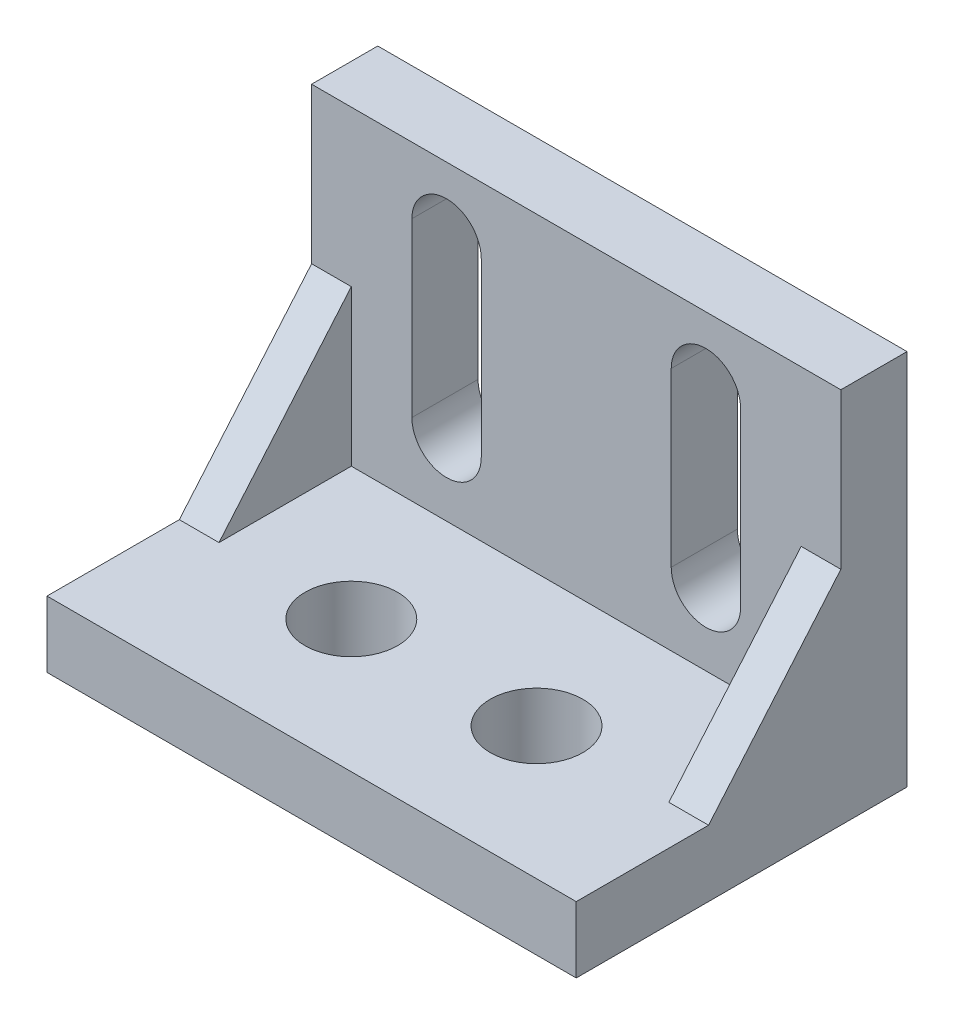
SolidWorks part; units mm, degrees
ref_plane "Front Plane" through (0, 0, 0) normal (0, 0, 1) x (1, 0, 0)
ref_plane "Top Plane" through (0, 0, 0) normal (0, 1, 0) x (1, 0, 0)
ref_plane "Right Plane" through (0, 0, 0) normal (1, 0, 0) x (0, 0, -1)
sketch "Sketch1" plane through (0, 0, 0) normal (0, 0, 1) x (1, 0, 0)
  line L0 (3.25, -4.85) -> (-3.25, -4.85) construction
  line L1 (-10, -10.9397) -> (10, -10.9397)
  line L2 (-10, -10.9397) -> (-10, 3.3116)
  line L3 (-10, 3.3116) -> (10, 3.3116)
  line L4 (10, -10.9397) -> (10, 3.3116)
  line L5 (0, -4.85) -> (0, -10.9397) construction
  line L6 (-4.9, -5.7035) -> (-4.9, 0.8035) construction
  line L7 (-62.56, -10.9397) -> (-56.86, -10.9397) construction
  line L8 (-6.2107, -5.7035) -> (-6.2107, 0.8035)
  line L9 (-3.5893, -5.7035) -> (-3.5893, 0.8035)
  line L10 (4.9, -5.7035) -> (4.9, 0.8035) construction
  line L11 (3.5893, -5.7035) -> (3.5893, 0.8035)
  line L12 (6.2107, -5.7035) -> (6.2107, 0.8035)
  arc A0 (-6.2107, -5.7035) -> (-3.5893, -5.7035) centre (-4.9, -5.7035) ccw
  arc A1 (-3.5893, 0.8035) -> (-6.2107, 0.8035) centre (-4.9, 0.8035) ccw
  arc A3 (3.5893, -5.7035) -> (6.2107, -5.7035) centre (4.9, -5.7035) ccw
  arc A4 (6.2107, 0.8035) -> (3.5893, 0.8035) centre (4.9, 0.8035) ccw
  point P0 (0, -4.85)
  point P14 (-4.9, -2.45)
  point P21 (4.9, -2.45)
  dimension "D1" = 20
extrude "Boss-Extrude1" add sketch "Sketch1" along normal blind 2.5 contours L1 L4 L3 L2
sketch "Sketch2" plane through (0, 0, 2.5) normal (0, 0, 1) x (1, 0, 0)
  line L0 (10, -10.9397) -> (10, 3.3116) construction
  line L1 (-10, -10.9397) -> (10, -10.9397)
  line L2 (-10, -10.9397) -> (-10, -8.4397)
  line L3 (-10, -8.4397) -> (10, -8.4397)
  line L4 (10, -10.9397) -> (10, -8.4397)
  dimension "D1" = 2.5
extrude "Boss-Extrude2" add sketch "Sketch2" along normal blind 10
sketch "Sketch3" plane through (10, 0, 0) normal (1, 0, 0) x (0, 0, -1)
  line L0 (-7.5, -8.4397) -> (-2.5, -2.564)
  line L1 (-12.5, -8.4397) -> (-2.5, -8.4397) construction
  line L2 (-2.5, -8.4397) -> (-2.5, 3.3116) construction
  line L3 (-2.5, -2.564) -> (-2.5, -8.4397)
  line L4 (-2.5, -8.4397) -> (-7.5, -8.4397)
extrude "Boss-Extrude5" add sketch "Sketch3" against normal blind 1.5
sketch "Sketch4" plane through (0, -8.4397, 0) normal (0, 1, 0) x (1, 0, 0)
  line L0 (8.5, -7.5) -> (3.5, -7.5) construction
  line L2 (3.5, -7.5) -> (3.5, -12.5) construction
  line L3 (10, -12.5) -> (-10, -12.5) construction
  circle A0 centre (3.5, -7.5) radius 1.75
  dimension "D1" = 3.5
extrude "Cut-Extrude1" cut sketch "Sketch4" against normal through all contours A0
ref_plane "Plane1" through (0, 0, 0) normal (-1, 0, 0) x (0, 0, 1)
mirror "Mirror1" about plane through (0, 0, 0) normal (-1, 0, 0) of "Cut-Extrude1", "Boss-Extrude5"
